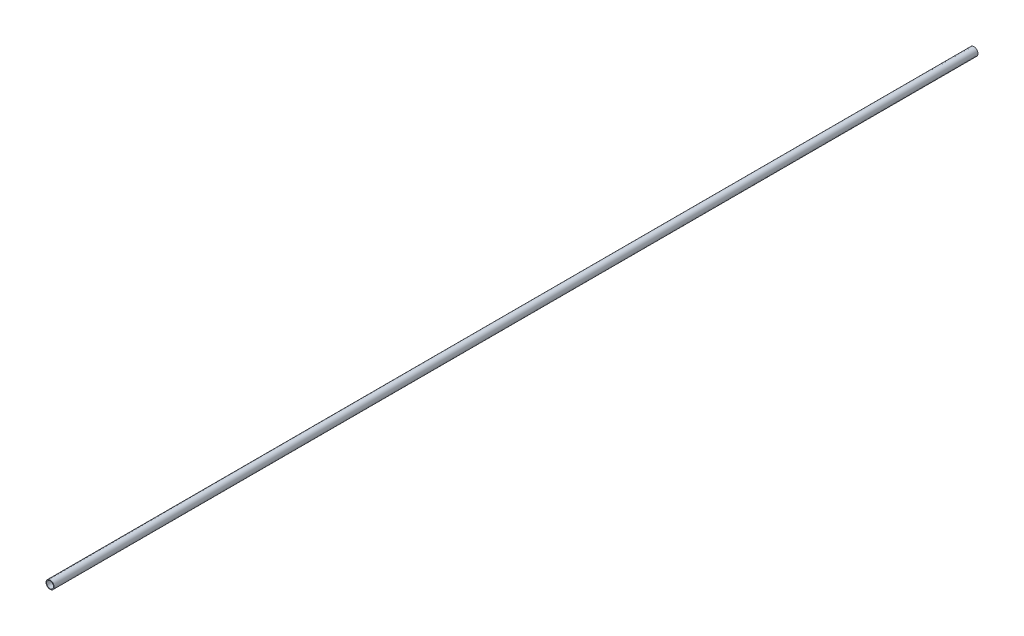
SolidWorks part; units mm, degrees
ref_plane "Front" through (0, 0, 0) normal (0, 0, 1) x (1, 0, 0)
ref_plane "Top" through (0, 0, 0) normal (0, 1, 0) x (1, 0, 0)
ref_plane "Side" through (0, 0, 0) normal (1, 0, 0) x (0, 0, -1)
other "Configuration Table"
sketch "PipeSketch" plane through (0, 0, 0) normal (0, 0, 1) x (1, 0, 0)
  circle A0 centre (0, 0) radius 24.13
  circle A1 centre (0, 0) radius 20.447
  dimension "OuterDiameter" = 48.26
  dimension "InnerDiameter" = 40.894
extrude "Extrusion" add sketch "PipeSketch" along normal blind 5486.4
sketch "FilterSketch" plane through (0, 0, 0) normal (0, 0, 1) x (1, 0, 0)
  circle A0 centre (0, 0) radius 19.05 construction
  dimension "NominalDiameter" = 38.1
